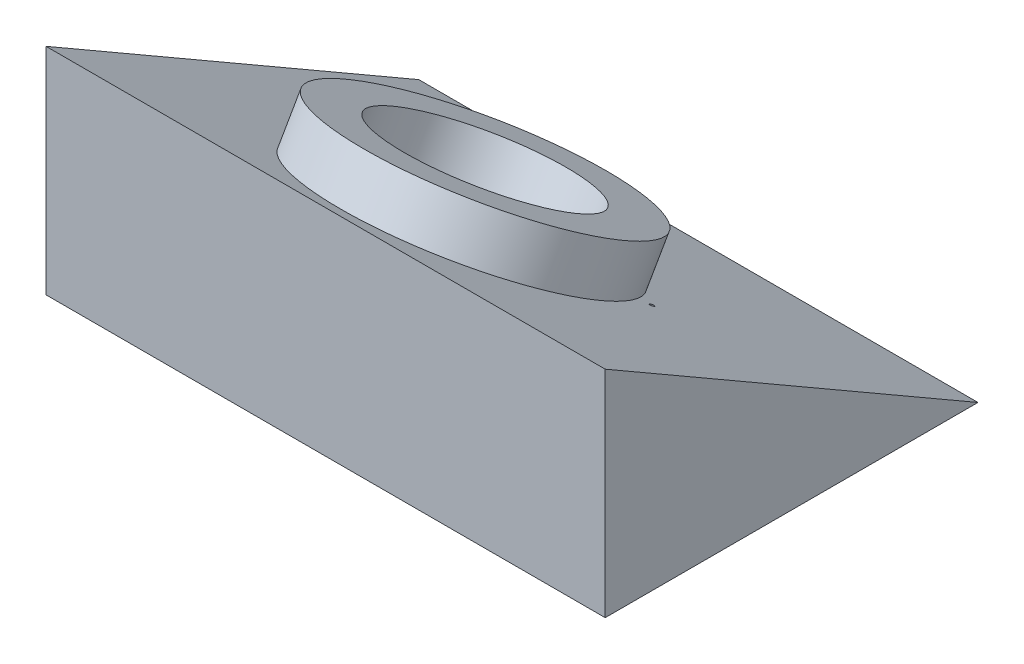
SolidWorks part; units mm, degrees
ref_plane "Front Plane" through (0, 0, 0) normal (0, 0, 1) x (1, 0, 0)
ref_plane "Top Plane" through (0, 0, 0) normal (0, 1, 0) x (1, 0, 0)
ref_plane "Right Plane" through (0, 0, 0) normal (1, 0, 0) x (0, 0, -1)
sketch "Sketch1" plane through (0, 0, 0) normal (0, 0, 1) x (1, 0, 0)
  line L0 (0, 7.62) -> (0, -7.62)
  arc A0 (0, -7.62) -> (0, 7.62) centre (0, 0) ccw
  dimension "D1" = 7.62
ref_plane "Plane1" through (0, -4.7625, 0) normal (0, 1, 0) x (1, 0, 0)
sketch "Sketch2" plane through (0, 0, 0) normal (0, 0, 1) x (1, 0, 0)
  line L0 (8.382, -4.7625) -> (-8.382, -4.7625) construction
  line L2 (-8.89, -4.7625) -> (8.89, -4.7625)
  line L3 (-8.89, -4.7625) -> (-8.89, 20.6375)
  line L4 (-8.89, 20.6375) -> (8.89, 20.6375)
  line L5 (8.89, -4.7625) -> (8.89, 20.6375)
  point P6 (0, -4.7625)
  dimension "D1" = 25.4
  dimension "D2" = 17.78
ref_plane "Plane2" through (0, -7.62, 0) normal (0, 1, 0) x (1, 0, 0)
sketch "Sketch9" plane through (0, -7.62, 0) normal (0, 1, 0) x (1, 0, 0)
  line L1 (-9.525, -6.35) -> (9.525, -6.35)
  line L2 (-9.525, -6.35) -> (-9.525, 6.35)
  line L3 (-9.525, 6.35) -> (9.525, 6.35)
  line L4 (9.525, -6.35) -> (9.525, 6.35)
  point P4 (0, -6.35)
  point P6 (9.525, 0)
  dimension "D1" = 19.05
  dimension "D2" = 12.7
extrude "Boss-Extrude1" add sketch "Sketch9" along normal blind 25.4
sketch "Sketch10" plane through (9.525, 0, 0) normal (1, 0, 0) x (0, 0, -1)
  line L0 (6.35, -7.62) -> (-6.35, -0.2877)
  line L1 (6.985, -7.62) -> (-6.985, -7.62) construction
  line L2 (6.35, 17.78) -> (6.35, -7.62) construction
  line L3 (-6.35, 17.78) -> (-6.35, -7.62) construction
  line L4 (-6.35, -0.2877) -> (-6.35, 22.86)
  line L5 (-6.35, 22.86) -> (6.35, 22.86)
  line L6 (6.35, 22.86) -> (6.35, -7.62)
  dimension "D1" = 30
  dimension "D2" = 30.48
extrude "Cut-Extrude1" cut sketch "Sketch10" against normal through all
sketch "Sketch11" plane through (0, -2.9654, 1.7121) normal (0, 0.866, -0.5) x (1, 0, 0)
  circle A0 centre (0, 0) radius 4.7625
  circle A1 centre (0, 0) radius 3.175
  dimension "D1" = 9.525
  dimension "D2" = 6.35
extrude "Boss-Extrude2" add sketch "Sketch11" along normal blind 1.5875
sketch "Sketch12" plane through (0, -7.62, 0) normal (0, -1, 0) x (1, 0, 0)
  line L0 (-9.525, 6.35) -> (9.525, 6.35) construction
  line L1 (-9.525, -6.35) -> (-9.525, 6.35) construction
  line L2 (9.525, 6.35) -> (9.525, -6.35) construction
  point P0 (-4.7625, 0)
  point P1 (4.7625, 0)
  point P6 (0, 0)
  dimension "D1" = 6.35
  dimension "D2" = 4.7625
  dimension "D3" = 4.7625
hole_wizard "#97 (0.0059) Diameter Hole1" positions "Sketch13" profile "Sketch14" hole size "#97" standard "ANSI Inch" end condition through all
sketch "Sketch13" plane through (0, -7.62, 0) normal (0, -1, 0) x (-1, 0, 0)
  point P0 (4.7625, 0)
  point P3 (-4.7625, 0)
sketch "Sketch14" plane through (-4.7625, -7.62, 0) normal (1, 0, 0) x (0, 0, -1)
  line L0 (0, 0) -> (0, 8.4107)
  line L1 (0, 8.4107) -> (0.0749, 8.4107)
  line L2 (0.0749, 8.4107) -> (0.0749, 1.2053)
  line L3 (0.0749, 1.2053) -> (1.5113, 0)
  line L5 (1.5113, 0) -> (0, 0)
  line L6 (-0.0749, 1.2053) -> (-1.5113, 0) construction
  line L11 (0, -6.35) -> (0, 107.95) construction
  dimension "Thru Hole Dia." = 0.1499
  dimension "Thru Hole Depth" = 8.4107
  dimension "Near C'Sink Dia." = 3.0226
  dimension "Near C'Sink Angle" = 100
